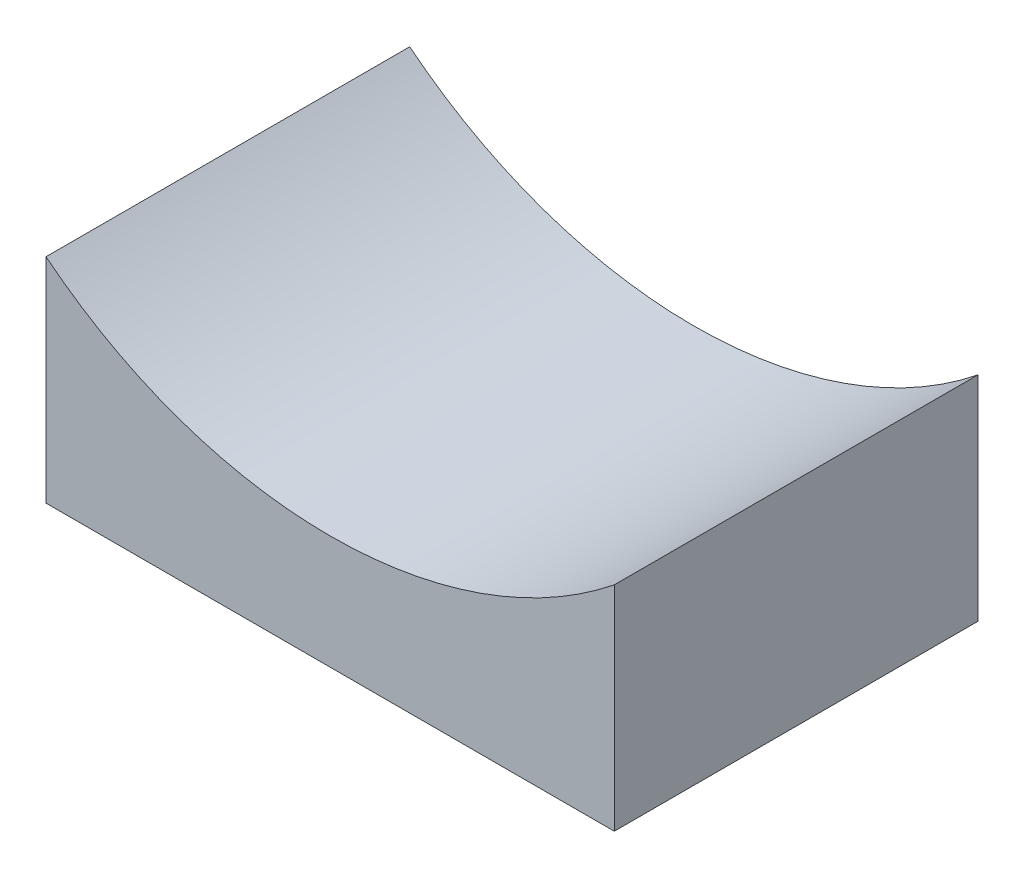
SolidWorks part; units mm, degrees
ref_plane "Front Plane" through (0, 0, 0) normal (0, 0, 1) x (1, 0, 0)
ref_plane "Top Plane" through (0, 0, 0) normal (0, 1, 0) x (1, 0, 0)
ref_plane "Right Plane" through (0, 0, 0) normal (1, 0, 0) x (0, 0, -1)
sketch "Sketch1" plane through (0, 0, 0) normal (0, 1, 0) x (1, 0, 0)
  line L1 (0, 0) -> (100, 0)
  line L2 (0, 0) -> (0, 64)
  line L3 (0, 64) -> (100, 64)
  line L4 (100, 0) -> (100, 64)
  dimension "D1" = 64
  dimension "D2" = 100
extrude "Boss-Extrude1" add sketch "Sketch1" along normal blind 80
sketch "Sketch2" plane through (0, 0, 0) normal (0, 0, 1) x (1, 0, 0)
  line L2 (0, 0) -> (100, 0) construction
  line L3 (0, 80) -> (100, 80) construction
  line L4 (-30, 100) -> (130, 100)
  arc A0 (-30, 100) -> (130, 100) centre (50, 100) ccw
  point P14 (50, 80)
  dimension "D1" = 80
  dimension "D2" = 100
extrude "Cut-Extrude1" cut sketch "Sketch2" against normal through all
